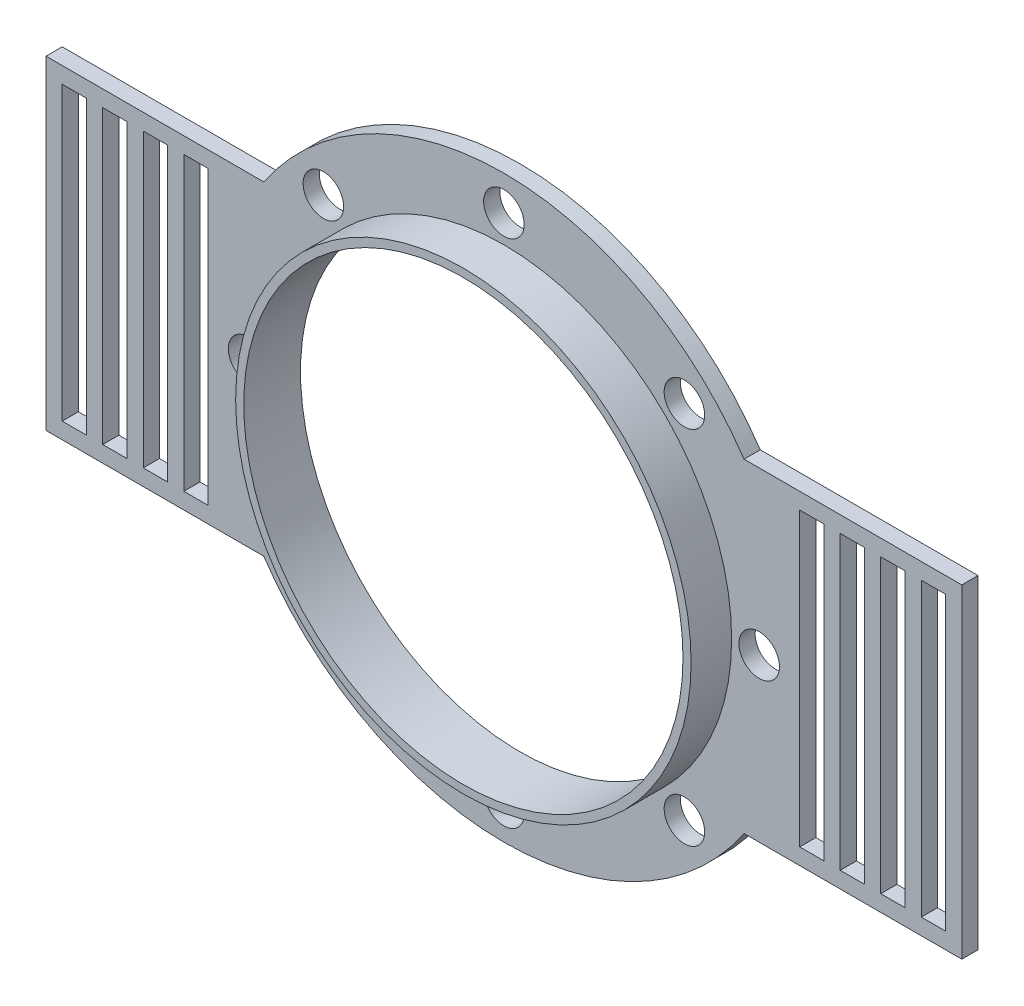
SolidWorks part; units mm, degrees
ref_plane "Alzado" through (0, 0, 0) normal (0, 0, 1) x (1, 0, 0)
ref_plane "Planta" through (0, 0, 0) normal (0, 1, 0) x (1, 0, 0)
ref_plane "Vista lateral" through (0, 0, 0) normal (1, 0, 0) x (0, 0, -1)
sketch "Croquis1" plane through (0, 0, 0) normal (0, 0, 1) x (1, 0, 0)
  line L0 (0, 0) -> (0, 31.5) construction
  line L1 (-56.5, 20) -> (-29.6321, 20)
  line L2 (-56.5, 20) -> (-56.5, -20)
  line L3 (-56.5, -20) -> (-29.6321, -20)
  line L5 (56.5, -20) -> (29.6321, -20)
  line L6 (56.5, 20) -> (56.5, -20)
  line L7 (56.5, 20) -> (29.6321, 20)
  line L8 (-49.5, 18) -> (-49.5, -18)
  line L9 (-54.5, 18) -> (-51.5, 18)
  line L10 (-54.5, 18) -> (-54.5, -18)
  line L11 (-54.5, -18) -> (-51.5, -18)
  line L12 (-51.5, 18) -> (-51.5, -18)
  line L13 (-49.5, 18) -> (-46.5, 18)
  line L14 (-46.5, 18) -> (-46.5, -18)
  line L15 (-49.5, -18) -> (-46.5, -18)
  line L16 (-44.5, 18) -> (-44.5, -18)
  line L17 (-44.5, 18) -> (-41.5, 18)
  line L18 (-41.5, 18) -> (-41.5, -18)
  line L19 (-44.5, -18) -> (-41.5, -18)
  line L20 (-39.5, 18) -> (-39.5, -18)
  line L21 (-39.5, 18) -> (-36.5, 18)
  line L22 (-36.5, 18) -> (-36.5, -18)
  line L23 (-39.5, -18) -> (-36.5, -18)
  line L24 (39.5, 18) -> (39.5, -18)
  line L25 (41.5, 18) -> (41.5, -18)
  line L26 (44.5, 18) -> (44.5, -18)
  line L27 (46.5, 18) -> (46.5, -18)
  line L28 (49.5, 18) -> (49.5, -18)
  line L29 (49.5, 18) -> (46.5, 18)
  line L30 (44.5, 18) -> (41.5, 18)
  line L31 (39.5, 18) -> (36.5, 18)
  line L32 (36.5, 18) -> (36.5, -18)
  line L33 (39.5, -18) -> (36.5, -18)
  line L34 (44.5, -18) -> (41.5, -18)
  line L35 (49.5, -18) -> (46.5, -18)
  line L36 (54.5, -18) -> (51.5, -18)
  line L37 (51.5, 18) -> (51.5, -18)
  line L38 (54.5, 18) -> (54.5, -18)
  line L39 (54.5, 18) -> (51.5, 18)
  circle A0 centre (0, 0) radius 27.1
  arc A1 (-29.6321, -20) -> (29.6321, -20) centre (0, 0) ccw
  circle A2 centre (31.5, 0) radius 2.5
  circle A3 centre (22.2739, -22.2739) radius 2.5
  circle A4 centre (0, -31.5) radius 2.5
  circle A5 centre (-22.2739, -22.2739) radius 2.5
  circle A6 centre (-31.5, 0) radius 2.5
  circle A7 centre (-22.2739, 22.2739) radius 2.5
  circle A8 centre (0, 31.5) radius 2.5
  circle A9 centre (22.2739, 22.2739) radius 2.5
  circle A10 centre (0, 0) radius 31.5 construction
  arc A11 (29.6321, 20) -> (-29.6321, 20) centre (0, 0) ccw
  point P22 (-56.5, 0)
  point P33 (-54.5, 0)
  dimension "D1" = 54.2
  dimension "D2" = 5
  dimension "D5" = 63
  dimension "D6" = 71.5
  dimension "D3" = 31.5
  dimension "D7" = 40
  dimension "D8" = 25
  dimension "D9" = 36
  dimension "D10" = 2
  dimension "D11" = 3
  dimension "D13" = 2
  dimension "D12" = 4
  dimension "D4" = 8
extrude "Saliente-Extruir1" add sketch "Croquis1" along normal blind 2
sketch "Croquis2" plane through (0, 0, 2) normal (0, 0, 1) x (1, 0, 0)
  circle A0 centre (0, 0) radius 27.1 construction
  circle A1 centre (0, 0) radius 27.1
  circle A2 centre (0, 0) radius 28.1
  dimension "D1" = 1
extrude "Saliente-Extruir2" add sketch "Croquis2" along normal blind 5
